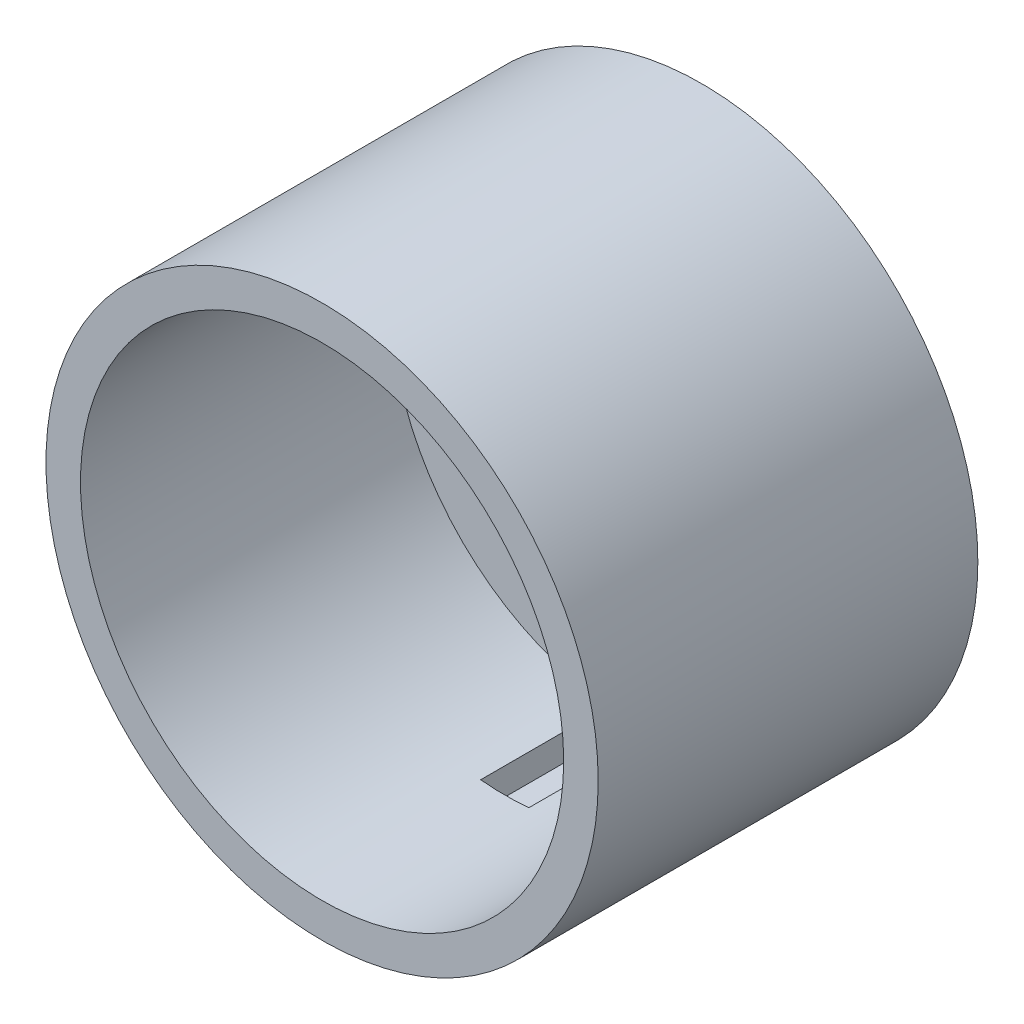
SolidWorks part; units mm, degrees
ref_plane "Plan de face" through (0, 0, 0) normal (0, 0, 1) x (1, 0, 0)
ref_plane "Plan de dessus" through (0, 0, 0) normal (0, 1, 0) x (1, 0, 0)
ref_plane "Plan de droite" through (0, 0, 0) normal (1, 0, 0) x (0, 0, -1)
sketch "Esquisse1" plane through (0, 0, 0) normal (0, 0, 1) x (1, 0, 0)
  circle A0 centre (0, 0) radius 16
extrude "Boss.-Extru.1" add sketch "Esquisse1" along normal blind 22
sketch "Esquisse2" plane through (0, 0, 0) normal (0, 0, 1) x (1, 0, 0)
  line L1 (-1.4, 15.5) -> (1.4, 15.5)
  line L2 (-1.4, 15.5) -> (-1.4, -15.5)
  line L3 (-1.4, -15.5) -> (1.4, -15.5)
  line L4 (1.4, 15.5) -> (1.4, -15.5)
  dimension "D1" = 31
  dimension "D2" = 2.8
  dimension "D3" = 1.4
  dimension "D4" = 15.5
extrude "Enlèv. mat.-Extru.1" cut sketch "Esquisse2" along normal blind 11.41
sketch "Esquisse3" plane through (0, 0, 0) normal (0, 0, -1) x (-1, 0, 0)
  line L0 (-1.4, -15.5) -> (-1.4, 15.5) construction
  line L1 (-1.4, -5.3) -> (1.4, -5.3)
  line L2 (-1.4, -5.3) -> (-1.4, -7.2)
  line L3 (-1.4, -7.2) -> (1.4, -7.2)
  line L4 (1.4, -5.3) -> (1.4, -7.2)
  line L5 (1.4, 15.5) -> (1.4, -15.5) construction
  line L6 (1.4, -15.5) -> (-1.4, -15.5) construction
  line L7 (-1.4, 15.5) -> (1.4, 15.5) construction
  line L8 (-1.4, 4.9) -> (1.4, 4.9)
  line L9 (-1.4, 4.9) -> (-1.4, 3)
  line L10 (-1.4, 3) -> (1.4, 3)
  line L11 (1.4, 4.9) -> (1.4, 3)
  dimension "D1" = 1.9
  dimension "D2" = 8.3
  dimension "D3" = 1.9
  dimension "D4" = 10.6
extrude "Boss.-Extru.2" add sketch "Esquisse3" against normal blind 5
sketch "Esquisse4" plane through (0, 0, 22) normal (0, 0, 1) x (1, 0, 0)
  circle A0 centre (0, 0) radius 14
extrude "Enlèv. mat.-Extru.2" cut sketch "Esquisse4" against normal blind 18
